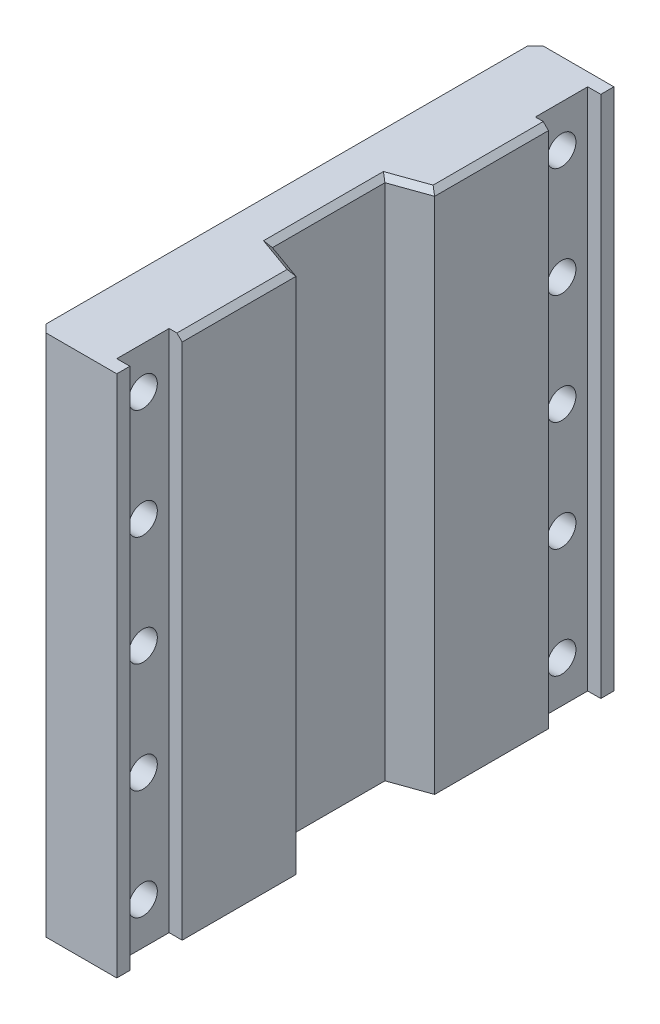
SolidWorks part; units mm, degrees
material "Carburized and nitrided special steel"
ref_plane "Piano frontale" through (0, 0, 0) normal (0, 0, 1) x (1, 0, 0)
ref_plane "Piano superiore" through (0, 0, 0) normal (0, 1, 0) x (1, 0, 0)
ref_plane "Piano destro" through (0, 0, 0) normal (1, 0, 0) x (0, 0, -1)
sketch "Schizzo1" plane through (0, 0, 0) normal (0, 1, 0) x (1, 0, 0)
  line L0 (0, -95) -> (0, 95)
  line L1 (0, 95) -> (30, 95)
  line L2 (30, 95) -> (30, 90)
  line L3 (30, 90) -> (25, 90)
  line L4 (25, 90) -> (25, 70)
  line L5 (25, 70) -> (30, 70)
  line L6 (30, 66) -> (30, 26.5)
  line L7 (0, 0) -> (80.8694, 0) construction
  line L8 (16, 21.5) -> (16, -21.5)
  line L9 (16, 21.5) -> (30, 26.5)
  line L10 (16, -21.5) -> (30, -26.5)
  line L11 (30, -66) -> (30, -26.5)
  line L12 (25, -70) -> (30, -70)
  line L13 (25, -90) -> (25, -70)
  line L14 (30, -90) -> (25, -90)
  line L15 (30, -95) -> (30, -90)
  line L16 (0, -95) -> (30, -95)
  line L17 (30, 66) -> (30, 70)
  line L18 (30, -66) -> (30, -70)
  point P14 (16, 0)
  dimension "D1" = 95
  dimension "D2" = 30
  dimension "D3" = 5
  dimension "D4" = 5
  dimension "D5" = 20
  dimension "D7" = 26.5
  dimension "D8" = 14
  dimension "D9" = 21.5
extrude "Estrusione1" add sketch "Schizzo1" along normal blind 200
hole_wizard "M10 Lamatura per vite a copertura cilindrica esagonale1" positions "Schizzo3" profile "Schizzo2" counterbore size "M10" standard "ISO" end condition through all
sketch "Schizzo3" plane through (0, 0, 0) normal (-1, 0, 0) x (0, 0, 1)
  line L0 (-95, 200) -> (95, 200) construction
  line L1 (95, 200) -> (95, 0) construction
  point P0 (80, 184)
  dimension "D1" = 16
  dimension "D2" = 15
sketch "Schizzo2" plane through (0, 184, 80) normal (0, 1, 0) x (0, 0, 1)
  line L0 (0, 0) -> (0, 30)
  line L1 (0, 30) -> (5.5, 30)
  line L3 (5.5, 30) -> (5.5, 10)
  line L4 (5.5, 10) -> (9, 10)
  line L5 (9, 10) -> (9, 0)
  line L7 (9, 0) -> (0, 0)
  line L11 (0, -6.35) -> (0, 107.95) construction
  dimension "Thru Hole Dia." = 11
  dimension "Thru Hole Depth" = 30
  dimension "C'Bore Dia." = 18
  dimension "C'Bore Depth" = 10
pattern_linear "Ripetizione a L1" count 5 spacing 42 along (0, -1, 0) count 2 spacing 160 along (0, 0, -1) of "M10 Lamatura per vite a copertura cilindrica esagonale1"
chamfer "Smusso1" distance 3 angle 45 2 edges at (0, 100, 95) (0, 100, -95)
chamfer "Smusso2" distance 2 angle 45 5 edges at (30, 200, 48.25) (23, 200, 24) (16, 200, 0) (23, 200, -24) (30, 200, -48.25)
